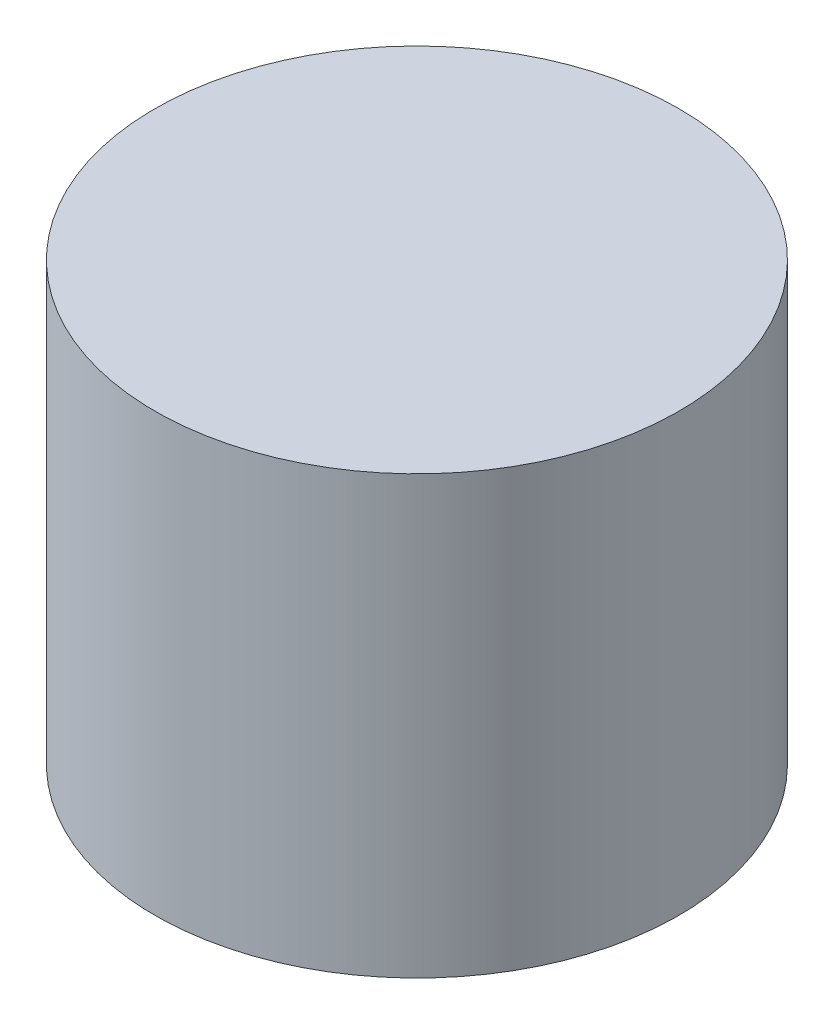
SolidWorks part; units mm, degrees
ref_plane "Front Plane" through (0, 0, 0) normal (0, 0, 1) x (1, 0, 0)
ref_plane "Top Plane" through (0, 0, 0) normal (0, 1, 0) x (1, 0, 0)
ref_plane "Right Plane" through (0, 0, 0) normal (1, 0, 0) x (0, 0, -1)
sketch "Reconstructed nominal axial profile" plane through (0, 0, 0) normal (0, 0, 1) x (1, 0, 0)
  line L0 (0, -500) -> (0, 50) construction
  line L1 (0, 0) -> (0, 10)
  line L2 (0, 10) -> (6, 10)
  line L3 (6, 10) -> (6, 0)
  line L4 (6, 0) -> (0, 0)
revolve "Native revolved geometry" add sketch "Reconstructed nominal axial profile" angle 360 about L0
